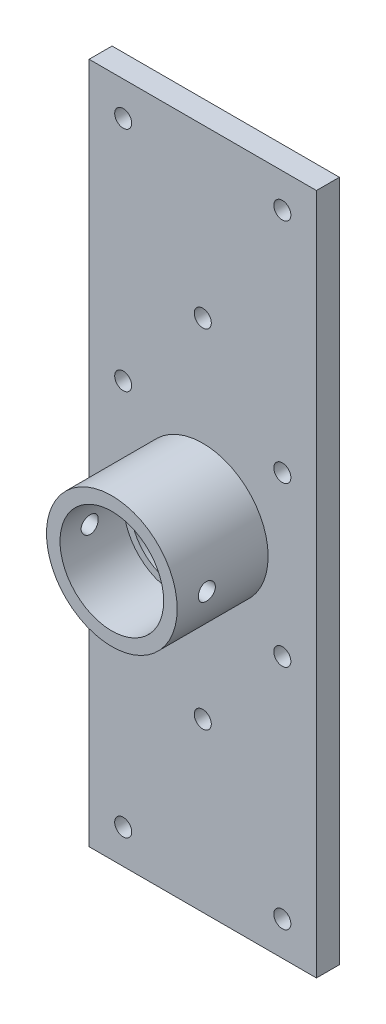
SolidWorks part; units mm, degrees
ref_plane "Front Plane" through (0, 0, 0) normal (0, 0, 1) x (1, 0, 0)
ref_plane "Top Plane" through (0, 0, 0) normal (0, 1, 0) x (1, 0, 0)
ref_plane "Right Plane" through (0, 0, 0) normal (1, 0, 0) x (0, 0, -1)
sketch "Sketch1" plane through (0, 0, 0) normal (0, 0, 1) x (1, 0, 0)
  line L5 (-31.75, 95.25) -> (31.75, 95.25)
  line L6 (-31.75, 95.25) -> (-31.75, -95.25)
  line L7 (-31.75, -95.25) -> (31.75, -95.25)
  line L8 (31.75, 95.25) -> (31.75, -95.25)
  line L9 (-31.75, 95.25) -> (31.75, -95.25) construction
  line L10 (-31.75, -95.25) -> (31.75, 95.25) construction
  point P5 (0, 0)
  dimension "D1" = 63.5
  dimension "D2" = 190.5
extrude "Boss-Extrude1" add sketch "Sketch1" along normal blind 4.7625 and the other way blind 1.651
sketch "Sketch3" plane through (0, 0, 4.7625) normal (0, 0, 1) x (1, 0, 0)
  circle A0 centre (0, 0) radius 6.35
  dimension "D1" = 12.7
extrude "Cut-Extrude1" cut sketch "Sketch3" against normal blind 0.508
sketch "Sketch4" plane through (0, 0, 4.7625) normal (0, 0, 1) x (1, 0, 0)
  circle A0 centre (0, 0) radius 18.2562
  dimension "D1" = 36.5125
extrude "Boss-Extrude2" add sketch "Sketch4" along normal blind 38.1 contours A0
sketch "Sketch5" plane through (0, 0, 42.8625) normal (0, 0, 1) x (1, 0, 0)
  circle A0 centre (0, 0) radius 12.4619
  dimension "D1" = 24.9237
extrude "Cut-Extrude2" cut sketch "Sketch5" against normal blind 38.1 contours A0
sketch "Sketch7" plane through (0, 0, 42.8625) normal (0, 0, 1) x (1, 0, 0)
  circle A0 centre (0, 0) radius 14.2875
  dimension "D1" = 28.575
extrude "Cut-Extrude3" cut sketch "Sketch7" against normal blind 30.48
hole_wizard "3/16 (0.1875) Diameter Hole1" positions "Sketch8" profile "Sketch9" hole size "3/16" standard "ANSI Inch" end condition through all
sketch "Sketch8" plane through (0, 0, 4.7625) normal (0, 0, 1) x (1, 0, 0)
  line L0 (31.75, 95.25) -> (-31.75, 95.25) construction
  line L1 (31.75, -95.25) -> (31.75, 95.25) construction
  line L2 (-31.75, 95.25) -> (-31.75, -95.25) construction
  line L3 (-31.75, -95.25) -> (31.75, -95.25) construction
  point P0 (-22.225, 85.725)
  point P2 (-22.225, -85.725)
  point P4 (22.225, -85.725)
  point P6 (22.225, 85.725)
  point P17 (0, 48.514)
  point P19 (0, -48.514)
  point P23 (-22.225, 22.225)
  point P26 (-22.225, -22.225)
  point P28 (22.225, -22.225)
  point P30 (22.225, 22.225)
  dimension "D1" = 9.525
  dimension "D2" = 9.525
  dimension "D3" = 9.525
  dimension "D4" = 9.525
  dimension "D5" = 9.525
  dimension "D6" = 9.525
  dimension "D7" = 9.525
  dimension "D8" = 9.525
  dimension "D9" = 48.514
  dimension "D10" = 48.514
  dimension "D11" = 63.5
  dimension "D12" = 63.5
  dimension "D13" = 63.5
  dimension "D14" = 63.5
sketch "Sketch9" plane through (-22.225, 85.725, 4.7625) normal (1, 0, 0) x (0, -1, 0)
  line L0 (0, 0) -> (0, 6.4135)
  line L1 (0, 6.4135) -> (2.3812, 6.4135)
  line L2 (2.3812, 6.4135) -> (2.3812, 0)
  line L5 (2.3812, 0) -> (0, 0)
  line L11 (0, -6.35) -> (0, 107.95) construction
  dimension "Thru Hole Dia." = 4.7625
  dimension "Thru Hole Depth" = 6.4135
sketch "Sketch10" plane through (0, 0, 4.7625) normal (0, 0, 1) x (1, 0, 0)
  line L0 (31.75, 31.75) -> (-31.75, 31.75)
  line L1 (31.75, -95.25) -> (31.75, 95.25) construction
  line L2 (-31.75, 95.25) -> (-31.75, -95.25) construction
  line L3 (31.75, -31.75) -> (-31.75, -31.75)
  point P8 (-31.75, 0)
  dimension "D1" = 31.75
  dimension "D2" = 31.75
sketch "Sketch13" plane through (0, 0, 42.8625) normal (0, 0, 1) x (1, 0, 0)
  circle A0 centre (0, 0) radius 14.478
  dimension "D1" = 28.956
extrude "Cut-Extrude4" cut sketch "Sketch13" against normal up to surface (30.48 mm away) up to face at (14.2875, 0, 12.3825)
sketch "Sketch14" plane through (0, 0, 42.8625) normal (0, 0, 1) x (1, 0, 0)
  circle A0 centre (0, 0) radius 18.2562
extrude "Cut-Extrude5" cut sketch "Sketch14" against normal blind 12.7
sketch "Sketch15" plane through (0, -95.25, 0) normal (0, -1, 0) x (-1, 0, 0)
hole_wizard "3/16 (0.1875) Diameter Hole3" positions "3DSketch7" profile "Sketch22" hole size "3/16" standard "ANSI Inch" end condition through all
sketch3d "3DSketch7"
  point P0 (18.2562, 0, 21.8735)
sketch "Sketch22" plane through (18.2562, 0, 21.8735) normal (0, 1, 0) x (0, 0, -1)
  line L0 (0, 0) -> (0, 50.0063)
  line L1 (0, 50.0063) -> (2.3812, 50.0063)
  line L2 (2.3812, 50.0063) -> (2.3812, 0)
  line L5 (2.3812, 0) -> (0, 0)
  line L11 (0, -6.35) -> (0, 107.95) construction
  dimension "Thru Hole Dia." = 4.7625
  dimension "Thru Hole Depth" = 50.0063
